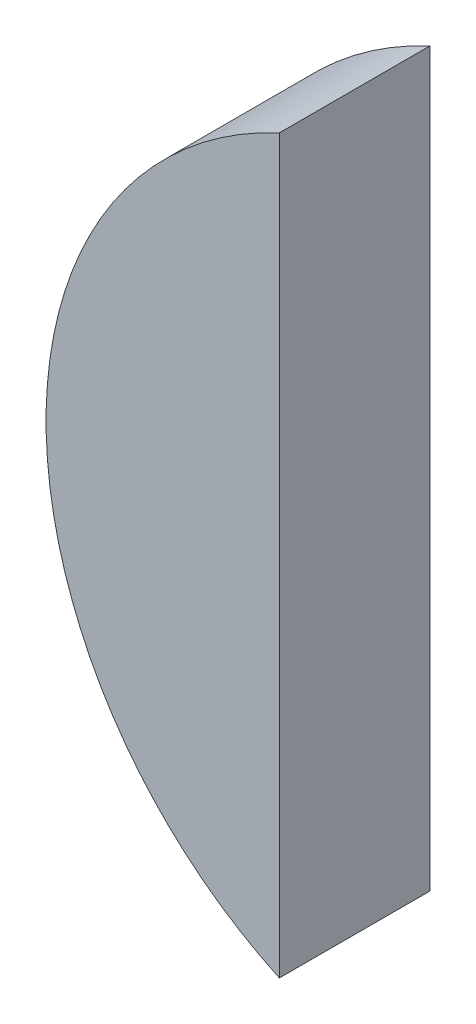
SolidWorks part; units mm, degrees
ref_plane "Front Plane" through (0, 0, 0) normal (0, 0, 1) x (1, 0, 0)
ref_plane "Top Plane" through (0, 0, 0) normal (0, 1, 0) x (1, 0, 0)
ref_plane "Right Plane" through (0, 0, 0) normal (1, 0, 0) x (0, 0, -1)
sketch "Sketch1" plane through (0, 0, 0) normal (0, 0, 1) x (1, 0, 0)
  line L0 (-21.59, 46.3483) -> (-21.59, -46.3483)
  arc A0 (-21.59, 46.3483) -> (-21.59, -46.3483) centre (0, 0) ccw
  dimension "D2" = 102.2604
  dimension "D1" = 21.59
extrude "Boss-Extrude1" add sketch "Sketch1" along normal mid plane 19.05 contours L0 A0
